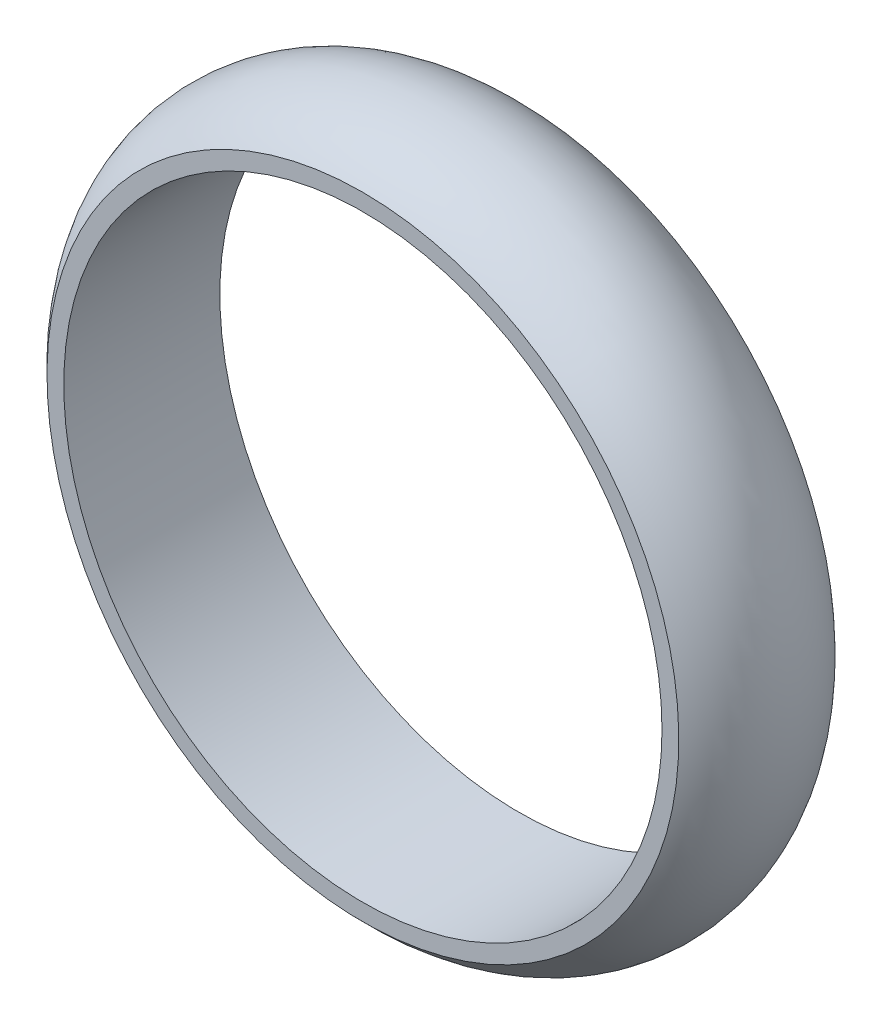
SolidWorks part; units mm, degrees
material "聚亚安酯(11671)"
ref_plane "前视基准面" through (0, 0, 0) normal (0, 0, 1) x (1, 0, 0)
ref_plane "上视基准面" through (0, 0, 0) normal (0, 1, 0) x (1, 0, 0)
ref_plane "右视基准面" through (0, 0, 0) normal (1, 0, 0) x (0, 0, -1)
sketch "草图1" plane through (0, 0, 0) normal (0, 0, 1) x (1, 0, 0)
  circle A0 centre (0, 0) radius 57.5
  circle A1 centre (0, 0) radius 67.5
  dimension "D1" = 115
  dimension "D2" = 135
extrude "凸台-拉伸1" add sketch "草图1" along normal blind 30
sketch "草图3" plane through (0, 0, 0) normal (1, 0, 0) x (0, 0, -1)
  line L0 (-30, 67.5) -> (-30, -67.5) construction
  line L1 (0, -67.5) -> (0, 67.5) construction
  line L2 (-30, 60.7288) -> (-30, 67.5)
  line L3 (-30, 67.5) -> (0, 67.5)
  line L4 (0, 67.5) -> (0, 60.7288)
  line L5 (-30, 47.5) -> (0, 47.5) construction
  line L6 (0, 0) -> (-30, 0) construction
  arc A0 (-30, 60.7288) -> (0, 60.7288) centre (-15, 47.5) cw
  point P7 (-15, 47.5)
  dimension "D2" = 20
revolve "切除-旋转1" cut sketch "草图3" angle 360 about L6
